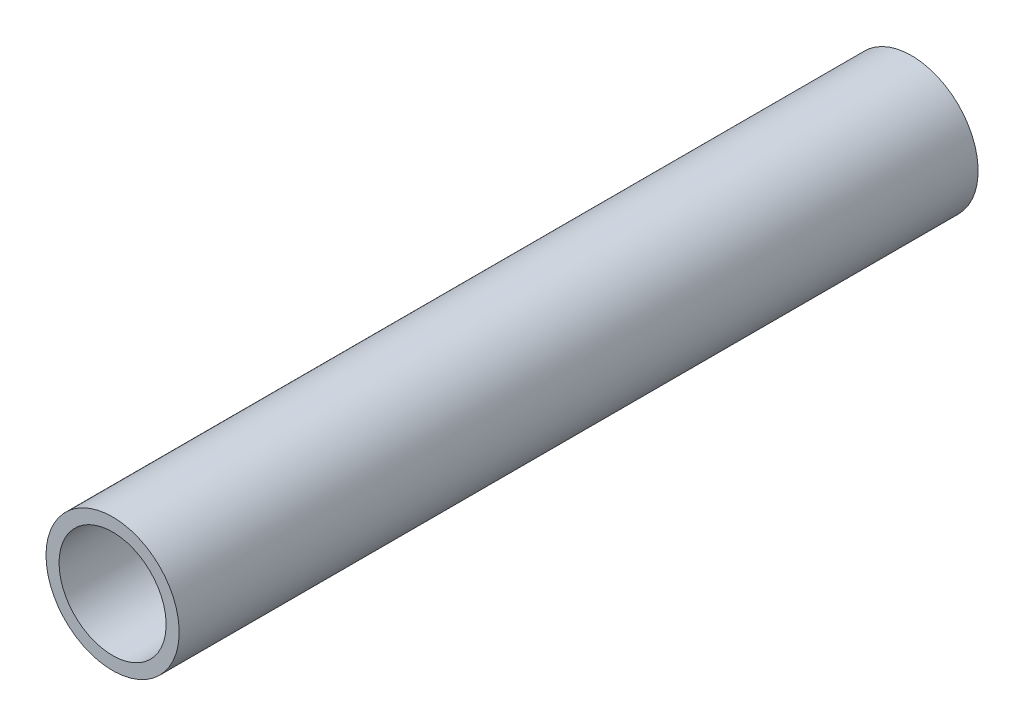
SolidWorks part; units mm, degrees
material "6061-T6 (SS)"
ref_plane "Front Plane" through (0, 0, 0) normal (0, 0, 1) x (1, 0, 0)
ref_plane "Top Plane" through (0, 0, 0) normal (0, 1, 0) x (1, 0, 0)
ref_plane "Right Plane" through (0, 0, 0) normal (1, 0, 0) x (0, 0, -1)
sketch "Sketch2" plane through (0, 0, 0) normal (0, 0, 1) x (1, 0, 0)
  circle A0 centre (0, 0) radius 6.35
  circle A1 centre (0, 0) radius 5.1054
  dimension "D1" = 12.7
  dimension "D2" = 10.2108
extrude "Boss-Extrude1" add sketch "Sketch2" along normal blind 76.2
